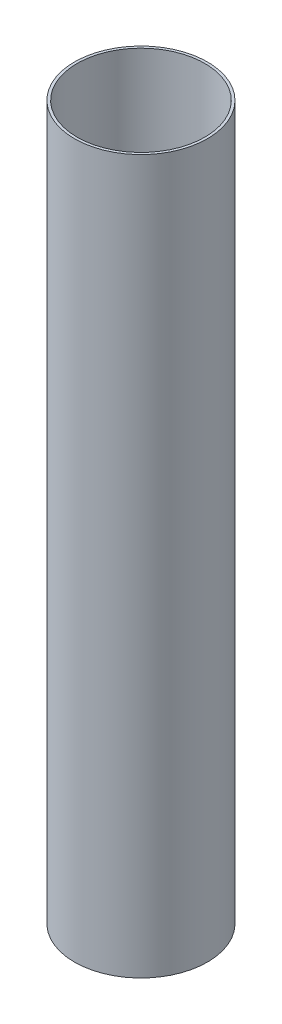
SolidWorks part; units mm, degrees
material "Wildman Fiberglass"
ref_plane "Front Plane" through (0, 0, 0) normal (0, 0, 1) x (1, 0, 0)
ref_plane "Top Plane" through (0, 0, 0) normal (0, 1, 0) x (1, 0, 0)
ref_plane "Right Plane" through (0, 0, 0) normal (1, 0, 0) x (0, 0, -1)
sketch "Sketch1" plane through (0, 0, 0) normal (0, 1, 0) x (1, 0, 0)
  circle A0 centre (0, 0) radius 27.3812
  circle A1 centre (0, 0) radius 28.4988
  dimension "D1" = 56.9976
  dimension "D2" = 54.7624
extrude "Boss-Extrude1" add sketch "Sketch1" along normal blind 305.562
equation "\"Length\"=12.03"
equation "\"D1@Boss-Extrude1\"=\"Length\""
